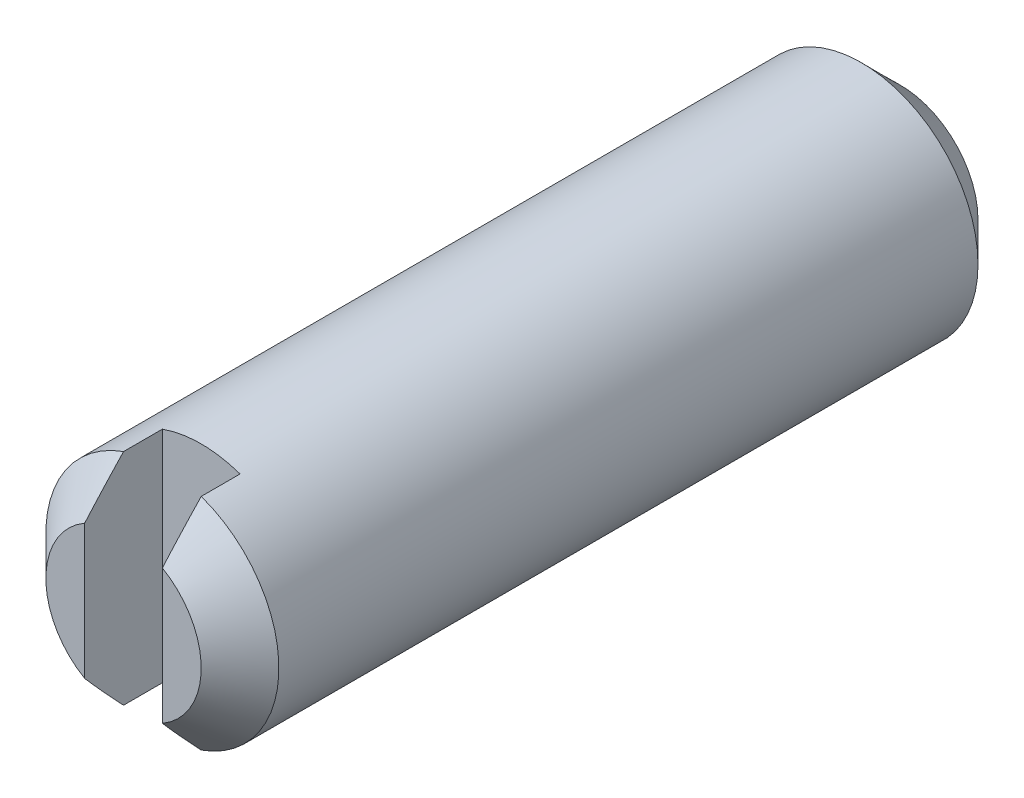
SolidWorks part; units mm, degrees
ref_plane "Plan de face" through (0, 0, 0) normal (0, 0, 1) x (1, 0, 0)
ref_plane "Plan de dessus" through (0, 0, 0) normal (0, 1, 0) x (1, 0, 0)
ref_plane "Plan de droite" through (0, 0, 0) normal (1, 0, 0) x (0, 0, -1)
sketch "Sketch1" plane through (0, 0, 0) normal (0, 0, 1) x (1, 0, 0)
  circle A0 centre (0, 0) radius 1.5
  dimension "D1" = 3
extrude "Boss-Extrude1" add sketch "Sketch1" along normal blind 10
cosmetic thread "Cosmetic Thread1" parameters "D2"=2
chamfer "Chamfer1" distance 0.5 angle 45 2 edges at (1.5, 0, 0) (1.5, 0, 10)
sketch "Sketch2" plane through (0, 0, 10) normal (0, 0, 1) x (1, 0, 0)
  line L0 (-0.5, 1.4142) -> (-0.5, -1.4142)
  line L1 (0.5, 1.4142) -> (0.5, -1.4142)
  arc A0 (0.5, 1.4142) -> (-0.5, 1.4142) centre (0, 0) ccw
  arc A1 (-0.5, -1.4142) -> (0.5, -1.4142) centre (0, 0) ccw
  dimension "D1" = 3
  dimension "D2" = 0.5
  dimension "D3" = 1
extrude "Cut-Extrude1" cut sketch "Sketch2" against normal blind 1
